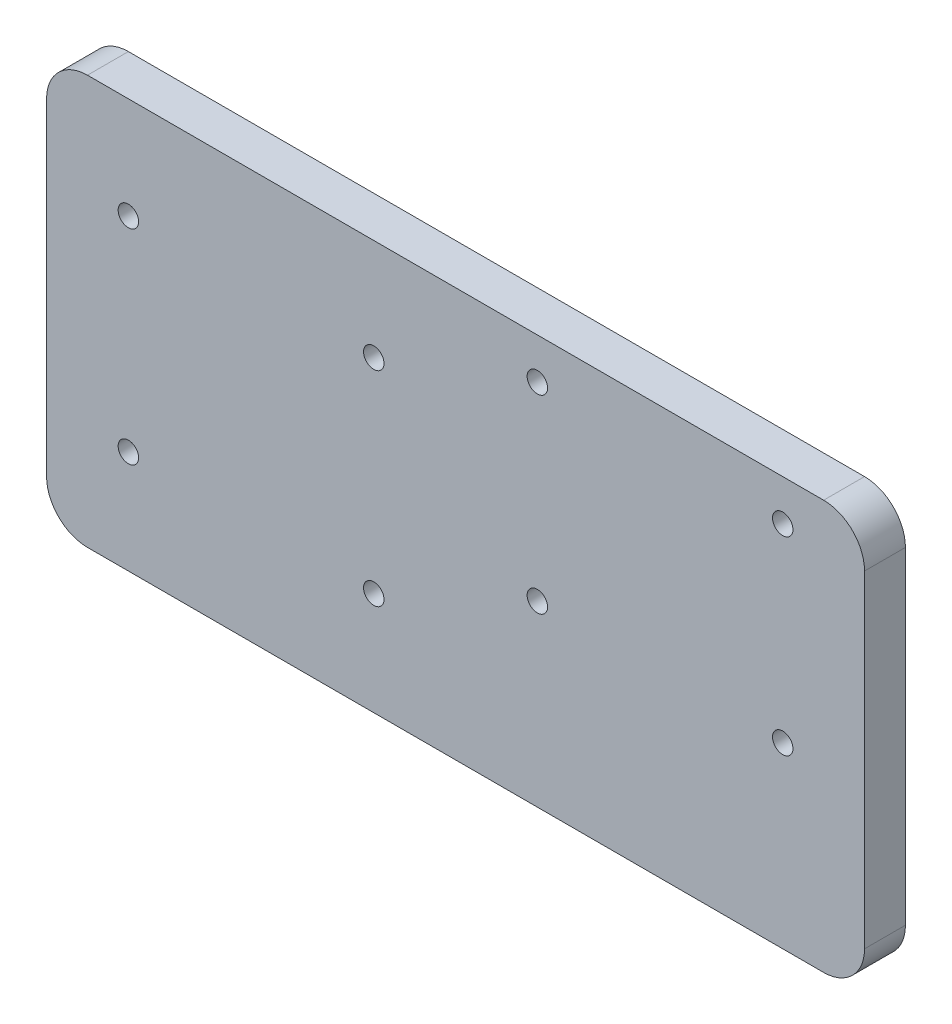
SolidWorks part; units mm, degrees
ref_plane "Front Plane" through (0, 0, 0) normal (0, 0, 1) x (1, 0, 0)
ref_plane "Top Plane" through (0, 0, 0) normal (0, 1, 0) x (1, 0, 0)
ref_plane "Right Plane" through (0, 0, 0) normal (1, 0, 0) x (0, 0, -1)
sketch "Sketch4" plane through (0, 0, 0) normal (0, 0, 1) x (1, 0, 0)
  line L1 (0, 0) -> (200, 0)
  line L2 (0, 0) -> (0, 100)
  line L3 (0, 100) -> (200, 100)
  line L4 (200, 0) -> (200, 100)
  dimension "D1" = 200
  dimension "D2" = 100
extrude "Boss-Extrude1" add sketch "Sketch4" along normal blind 10
sketch "Sketch6" plane through (0, 0, 10) normal (0, 0, 1) x (1, 0, 0)
  line L0 (50, 83.464) -> (50, 16.814)
  line L1 (0, 100) -> (0, 0) construction
  line L3 (80, 83.464) -> (80, 66.928)
  line L4 (0, 66.928) -> (200, 66.928)
  line L5 (200, 0) -> (200, 100) construction
  line L6 (0, 33.628) -> (200, 33.628)
  line L7 (200, 100) -> (0, 100) construction
  line L8 (100, 100) -> (100, 0)
  line L9 (0, 0) -> (200, 0) construction
  line L10 (80, 16.814) -> (80, 33.628)
  line L11 (20, 16.814) -> (20, 33.628)
  line L12 (35, 83.464) -> (35, 16.814)
  line L13 (20, 16.814) -> (80, 16.814)
  line L14 (20, 83.464) -> (20, 66.928)
  line L15 (80, 75.196) -> (20, 75.196)
  line L16 (20, 25.221) -> (80, 25.221)
  line L17 (20, 83.464) -> (50, 83.464)
  line L18 (50, 83.464) -> (80, 83.464)
  line L19 (65, 83.464) -> (65, 16.814)
  line L20 (100, 100) -> (120, 100)
  line L21 (200, 100) -> (180, 100)
  line L22 (120, 100) -> (120, 33.628)
  line L23 (180, 100) -> (180, 33.628)
  line L24 (120, 100) -> (120, 90)
  line L25 (120, 90) -> (180, 90)
  line L26 (120, 33.628) -> (120, 43.628)
  line L27 (120, 43.628) -> (180, 43.628)
hole_wizard "CBORE for M6 Hex Head Cap Screw7" positions "Sketch40" profile "Sketch39" counterbore size "M6" standard "ANSI Metric"
sketch "Sketch40" plane through (0, 0, 0) normal (0, 0, -1) x (-1, 0, 0)
  point P0 (-80, 83.464)
sketch "Sketch39" plane through (80, 83.464, 0) normal (1, 0, 0) x (0, 1, 0)
  line L0 (0, 0) -> (0, 9.8026)
  line L1 (0, 9.8026) -> (3, 8)
  line L2 (3, 8) -> (3, 2)
  line L3 (3, 2) -> (4, 2)
  line L4 (4, 2) -> (4, 0)
  line L5 (4, 0) -> (0, 0)
  line L10 (0, 9.8026) -> (-3, 8) construction
  line L11 (0, -6.35) -> (0, 107.95) construction
  dimension "Hole Dia." = 6
  dimension "Hole Depth" = 8
  dimension "C'Bore Dia." = 8
  dimension "C'Bore Depth" = 2
  dimension "Drill Angle" = 118
hole_wizard "CBORE for M6 Hex Head Cap Screw8" positions "Sketch42" profile "Sketch41" counterbore size "M6" standard "ANSI Metric"
sketch "Sketch42" plane through (0, 0, 0) normal (0, 0, -1) x (-1, 0, 0)
  point P0 (-20, 83.464)
sketch "Sketch41" plane through (20, 83.464, 0) normal (1, 0, 0) x (0, 1, 0)
  line L0 (0, 0) -> (0, 9.8026)
  line L1 (0, 9.8026) -> (3, 8)
  line L2 (3, 8) -> (3, 2)
  line L3 (3, 2) -> (4, 2)
  line L4 (4, 2) -> (4, 0)
  line L5 (4, 0) -> (0, 0)
  line L10 (0, 9.8026) -> (-3, 8) construction
  line L11 (0, -6.35) -> (0, 107.95) construction
  dimension "Hole Dia." = 6
  dimension "Hole Depth" = 8
  dimension "C'Bore Dia." = 8
  dimension "C'Bore Depth" = 2
  dimension "Drill Angle" = 118
hole_wizard "CBORE for M6 Hex Head Cap Screw9" positions "Sketch44" profile "Sketch43" counterbore size "M6" standard "ANSI Metric"
sketch "Sketch44" plane through (0, 0, 0) normal (0, 0, -1) x (-1, 0, 0)
  point P0 (-20, 16.814)
sketch "Sketch43" plane through (20, 16.814, 0) normal (1, 0, 0) x (0, 1, 0)
  line L0 (0, 0) -> (0, 9.8026)
  line L1 (0, 9.8026) -> (3, 8)
  line L2 (3, 8) -> (3, 2)
  line L3 (3, 2) -> (4, 2)
  line L4 (4, 2) -> (4, 0)
  line L5 (4, 0) -> (0, 0)
  line L10 (0, 9.8026) -> (-3, 8) construction
  line L11 (0, -6.35) -> (0, 107.95) construction
  dimension "Hole Dia." = 6
  dimension "Hole Depth" = 8
  dimension "C'Bore Dia." = 8
  dimension "C'Bore Depth" = 2
  dimension "Drill Angle" = 118
hole_wizard "CBORE for M6 Hex Head Cap Screw10" positions "Sketch46" profile "Sketch45" counterbore size "M6" standard "ANSI Metric"
sketch "Sketch46" plane through (0, 0, 0) normal (0, 0, -1) x (-1, 0, 0)
  point P0 (-80, 16.814)
sketch "Sketch45" plane through (80, 16.814, 0) normal (1, 0, 0) x (0, 1, 0)
  line L0 (0, 0) -> (0, 9.8026)
  line L1 (0, 9.8026) -> (3, 8)
  line L2 (3, 8) -> (3, 2)
  line L3 (3, 2) -> (4, 2)
  line L4 (4, 2) -> (4, 0)
  line L5 (4, 0) -> (0, 0)
  line L10 (0, 9.8026) -> (-3, 8) construction
  line L11 (0, -6.35) -> (0, 107.95) construction
  dimension "Hole Dia." = 6
  dimension "Hole Depth" = 8
  dimension "C'Bore Dia." = 8
  dimension "C'Bore Depth" = 2
  dimension "Drill Angle" = 118
hole_wizard "Ø1.0 (1) Diameter Hole7" positions "Sketch48" profile "Sketch47" hole size "Ø1.0" standard "ANSI Metric"
sketch "Sketch48" plane through (0, 0, 10) normal (0, 0, 1) x (1, 0, 0)
  point P0 (20, 75.196)
sketch "Sketch47" plane through (20, 75.196, 10) normal (1, 0, 0) x (0, -1, 0)
  line L0 (0, 0) -> (0, 9.5022)
  line L1 (0, 9.5022) -> (2.5, 8)
  line L2 (2.5, 8) -> (2.5, 0)
  line L5 (2.5, 0) -> (0, 0)
  line L10 (0, 9.5022) -> (-2.5, 8) construction
  line L11 (0, -6.35) -> (0, 107.95) construction
  dimension "Hole Dia." = 5
  dimension "Hole Depth" = 8
  dimension "Drill Angle" = 118
hole_wizard "Ø1.0 (1) Diameter Hole8" positions "Sketch50" profile "Sketch49" hole size "Ø1.0" standard "ANSI Metric"
sketch "Sketch50" plane through (0, 0, 10) normal (0, 0, 1) x (1, 0, 0)
  point P0 (80, 75.196)
sketch "Sketch49" plane through (80, 75.196, 10) normal (1, 0, 0) x (0, -1, 0)
  line L0 (0, 0) -> (0, 9.5022)
  line L1 (0, 9.5022) -> (2.5, 8)
  line L2 (2.5, 8) -> (2.5, 0)
  line L5 (2.5, 0) -> (0, 0)
  line L10 (0, 9.5022) -> (-2.5, 8) construction
  line L11 (0, -6.35) -> (0, 107.95) construction
  dimension "Hole Dia." = 5
  dimension "Hole Depth" = 8
  dimension "Drill Angle" = 118
hole_wizard "Ø1.0 (1) Diameter Hole9" positions "Sketch52" profile "Sketch51" hole size "Ø1.0" standard "ANSI Metric"
sketch "Sketch52" plane through (0, 0, 10) normal (0, 0, 1) x (1, 0, 0)
  point P0 (20, 25.221)
sketch "Sketch51" plane through (20, 25.221, 10) normal (1, 0, 0) x (0, -1, 0)
  line L0 (0, 0) -> (0, 9.5022)
  line L1 (0, 9.5022) -> (2.5, 8)
  line L2 (2.5, 8) -> (2.5, 0)
  line L5 (2.5, 0) -> (0, 0)
  line L10 (0, 9.5022) -> (-2.5, 8) construction
  line L11 (0, -6.35) -> (0, 107.95) construction
  dimension "Hole Dia." = 5
  dimension "Hole Depth" = 8
  dimension "Drill Angle" = 118
hole_wizard "Ø1.0 (1) Diameter Hole10" positions "Sketch54" profile "Sketch53" hole size "Ø1.0" standard "ANSI Metric"
sketch "Sketch54" plane through (0, 0, 10) normal (0, 0, 1) x (1, 0, 0)
  point P0 (80, 25.221)
sketch "Sketch53" plane through (80, 25.221, 10) normal (1, 0, 0) x (0, -1, 0)
  line L0 (0, 0) -> (0, 9.5022)
  line L1 (0, 9.5022) -> (2.5, 8)
  line L2 (2.5, 8) -> (2.5, 0)
  line L5 (2.5, 0) -> (0, 0)
  line L10 (0, 9.5022) -> (-2.5, 8) construction
  line L11 (0, -6.35) -> (0, 107.95) construction
  dimension "Hole Dia." = 5
  dimension "Hole Depth" = 8
  dimension "Drill Angle" = 118
hole_wizard "Ø5.0 (5) Diameter Hole1" positions "Sketch58" profile "Sketch57" hole size "Ø5.0" standard "ANSI Metric"
sketch "Sketch58" plane through (0, 0, 10) normal (0, 0, 1) x (1, 0, 0)
  point P0 (120, 90)
sketch "Sketch57" plane through (120, 90, 10) normal (1, 0, 0) x (0, -1, 0)
  line L0 (0, 0) -> (0, 9.5022)
  line L1 (0, 9.5022) -> (2.5, 8)
  line L2 (2.5, 8) -> (2.5, 0)
  line L5 (2.5, 0) -> (0, 0)
  line L10 (0, 9.5022) -> (-2.5, 8) construction
  line L11 (0, -6.35) -> (0, 107.95) construction
  dimension "Hole Dia." = 5
  dimension "Hole Depth" = 8
  dimension "Drill Angle" = 118
hole_wizard "Ø5.0 (5) Diameter Hole2" positions "Sketch60" profile "Sketch59" hole size "Ø5.0" standard "ANSI Metric"
sketch "Sketch60" plane through (0, 0, 10) normal (0, 0, 1) x (1, 0, 0)
  point P0 (180, 90)
sketch "Sketch59" plane through (180, 90, 10) normal (1, 0, 0) x (0, -1, 0)
  line L0 (0, 0) -> (0, 9.5022)
  line L1 (0, 9.5022) -> (2.5, 8)
  line L2 (2.5, 8) -> (2.5, 0)
  line L5 (2.5, 0) -> (0, 0)
  line L10 (0, 9.5022) -> (-2.5, 8) construction
  line L11 (0, -6.35) -> (0, 107.95) construction
  dimension "Hole Dia." = 5
  dimension "Hole Depth" = 8
  dimension "Drill Angle" = 118
hole_wizard "Ø5.0 (5) Diameter Hole3" positions "Sketch62" profile "Sketch61" hole size "Ø5.0" standard "ANSI Metric"
sketch "Sketch62" plane through (0, 0, 10) normal (0, 0, 1) x (1, 0, 0)
  point P0 (120, 43.628)
sketch "Sketch61" plane through (120, 43.628, 10) normal (1, 0, 0) x (0, -1, 0)
  line L0 (0, 0) -> (0, 9.5022)
  line L1 (0, 9.5022) -> (2.5, 8)
  line L2 (2.5, 8) -> (2.5, 0)
  line L5 (2.5, 0) -> (0, 0)
  line L10 (0, 9.5022) -> (-2.5, 8) construction
  line L11 (0, -6.35) -> (0, 107.95) construction
  dimension "Hole Dia." = 5
  dimension "Hole Depth" = 8
  dimension "Drill Angle" = 118
hole_wizard "Ø5.0 (5) Diameter Hole5" positions "Sketch68" profile "Sketch67" hole size "Ø5.0" standard "ANSI Metric"
sketch "Sketch68" plane through (0, 0, 10) normal (0, 0, 1) x (1, 0, 0)
  point P0 (180, 43.628)
sketch "Sketch67" plane through (180, 43.628, 10) normal (1, 0, 0) x (0, -1, 0)
  line L0 (0, 0) -> (0, 9.5022)
  line L1 (0, 9.5022) -> (2.5, 8)
  line L2 (2.5, 8) -> (2.5, 0)
  line L5 (2.5, 0) -> (0, 0)
  line L10 (0, 9.5022) -> (-2.5, 8) construction
  line L11 (0, -6.35) -> (0, 107.95) construction
  dimension "Hole Dia." = 5
  dimension "Hole Depth" = 8
  dimension "Drill Angle" = 118
fillet "Fillet1" radius 10 1 edges at (0, 100, 5)
fillet "Fillet2" radius 10 1 edges at (0, 0, 5)
fillet "Fillet3" radius 10 1 edges at (200, 0, 5)
fillet "Fillet4" radius 10 1 edges at (200, 100, 5)
hole_wizard "CBORE for M6 Hex Head Cap Screw3" positions "Sketch32" profile "Sketch31" counterbore size "M6" standard "ANSI Metric"
sketch "Sketch32" plane through (0, 0, 0) normal (0, 0, -1) x (-1, 0, 0)
  point P0 (-80, 16.814)
sketch "Sketch31" plane through (80, 16.814, 0) normal (1, 0, 0) x (0, 1, 0)
  line L0 (0, 0) -> (0, 9.8026)
  line L1 (0, 9.8026) -> (3, 8)
  line L2 (3, 8) -> (3, 2)
  line L3 (3, 2) -> (4, 2)
  line L4 (4, 2) -> (4, 0)
  line L5 (4, 0) -> (0, 0)
  line L10 (0, 9.8026) -> (-3, 8) construction
  line L11 (0, -6.35) -> (0, 107.95) construction
  dimension "Hole Dia." = 6
  dimension "Hole Depth" = 8
  dimension "C'Bore Dia." = 8
  dimension "C'Bore Depth" = 2
  dimension "Drill Angle" = 118
hole_wizard "CBORE for M6 Hex Head Cap Screw4" positions "Sketch34" profile "Sketch33" counterbore size "M6" standard "ANSI Metric"
sketch "Sketch34" plane through (0, 0, 0) normal (0, 0, -1) x (-1, 0, 0)
  point P0 (-20, 16.814)
sketch "Sketch33" plane through (20, 16.814, 0) normal (1, 0, 0) x (0, 1, 0)
  line L0 (0, 0) -> (0, 9.8026)
  line L1 (0, 9.8026) -> (3, 8)
  line L2 (3, 8) -> (3, 2)
  line L3 (3, 2) -> (4, 2)
  line L4 (4, 2) -> (4, 0)
  line L5 (4, 0) -> (0, 0)
  line L10 (0, 9.8026) -> (-3, 8) construction
  line L11 (0, -6.35) -> (0, 107.95) construction
  dimension "Hole Dia." = 6
  dimension "Hole Depth" = 8
  dimension "C'Bore Dia." = 8
  dimension "C'Bore Depth" = 2
  dimension "Drill Angle" = 118
hole_wizard "CBORE for M6 Hex Head Cap Screw6" positions "Sketch38" profile "Sketch37" counterbore size "M6" standard "ANSI Metric"
sketch "Sketch38" plane through (0, 0, 0) normal (0, 0, -1) x (-1, 0, 0)
  point P0 (-20, 83.464)
sketch "Sketch37" plane through (20, 83.464, 0) normal (1, 0, 0) x (0, 1, 0)
  line L0 (0, 0) -> (0, 9.8026)
  line L1 (0, 9.8026) -> (3, 8)
  line L2 (3, 8) -> (3, 2)
  line L3 (3, 2) -> (4, 2)
  line L4 (4, 2) -> (4, 0)
  line L5 (4, 0) -> (0, 0)
  line L10 (0, 9.8026) -> (-3, 8) construction
  line L11 (0, -6.35) -> (0, 107.95) construction
  dimension "Hole Dia." = 6
  dimension "Hole Depth" = 8
  dimension "C'Bore Dia." = 8
  dimension "C'Bore Depth" = 2
  dimension "Drill Angle" = 118
